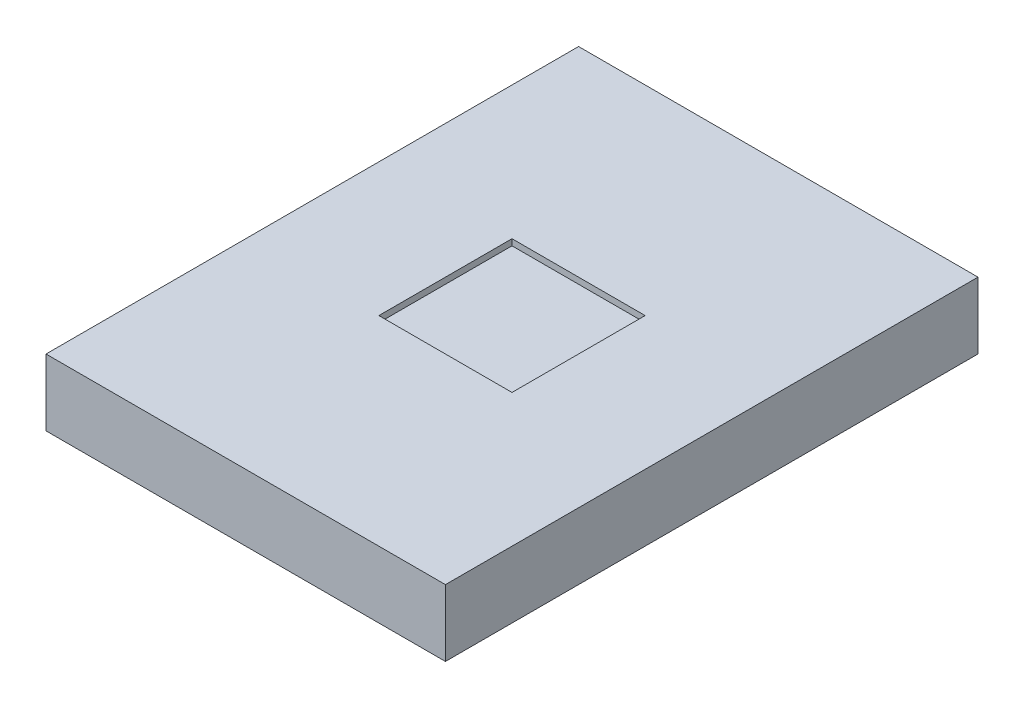
SolidWorks part; units mm, degrees
ref_plane "Front Plane" through (0, 0, 0) normal (0, 0, 1) x (1, 0, 0)
ref_plane "Top Plane" through (0, 0, 0) normal (0, 1, 0) x (1, 0, 0)
ref_plane "Right Plane" through (0, 0, 0) normal (1, 0, 0) x (0, 0, -1)
sketch "Sketch1" plane through (0, 0, 0) normal (0, 1, 0) x (1, 0, 0)
  line L0 (-1.0094, 43.7871) -> (-1.0094, -30.7359) construction
  line L1 (-42.6922, 0.2753) -> (43.988, 0.2753) construction
  line L2 (-16.0094, -19.7247) -> (13.9906, -19.7247)
  line L3 (-16.0094, -19.7247) -> (-16.0094, 20.2753)
  line L4 (-16.0094, 20.2753) -> (13.9906, 20.2753)
  line L5 (13.9906, -19.7247) -> (13.9906, 20.2753)
  dimension "D1" = 30
  dimension "D2" = 40
extrude "Boss-Extrude1" add sketch "Sketch1" along normal blind 5
sketch "Sketch2" plane through (0, 5, 0) normal (0, 1, 0) x (1, 0, 0)
  line L0 (13.9906, 20.2753) -> (-16.0094, 20.2753) construction
  line L1 (-6.0094, 5.2753) -> (3.9906, 5.2753)
  line L2 (-6.0094, 5.2753) -> (-6.0094, -4.7247)
  line L3 (-6.0094, -4.7247) -> (3.9906, -4.7247)
  line L4 (3.9906, 5.2753) -> (3.9906, -4.7247)
  line L5 (-16.0094, 20.2753) -> (-16.0094, -19.7247) construction
  dimension "D1" = 15
  dimension "D2" = 10
  dimension "D3" = 10
  dimension "D4" = 10
extrude "Cut-Extrude1" cut sketch "Sketch2" against normal blind 0.465
